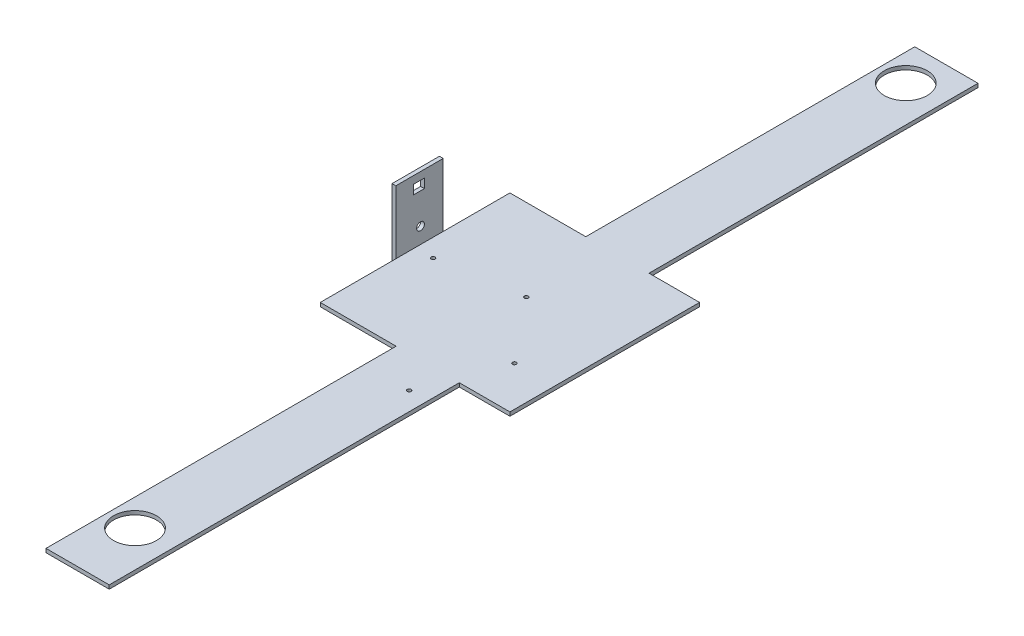
SolidWorks part; units mm, degrees
ref_plane "Front Plane" through (0, 0, 0) normal (0, 0, 1) x (1, 0, 0)
ref_plane "Top Plane" through (0, 0, 0) normal (0, 1, 0) x (1, 0, 0)
ref_plane "Right Plane" through (0, 0, 0) normal (1, 0, 0) x (0, 0, -1)
sketch "Sketch1" plane through (0, 0, 0) normal (0, 1, 0) x (1, 0, 0)
  line L0 (-140.4501, 142.2012) -> (-100.4501, 142.2012)
  line L1 (-250.4501, 142.2012) -> (-200.4501, 142.2012)
  line L2 (-250.4501, 142.2012) -> (-250.4501, -7.7988)
  line L3 (-250.4501, -7.7988) -> (-190.4501, -7.7988)
  line L4 (-100.4501, 142.2012) -> (-100.4501, -7.7988)
  line L6 (-140.4501, -7.7988) -> (-140.4501, -284.718)
  line L7 (-140.4501, -284.718) -> (-190.4501, -284.718)
  line L8 (-190.4501, -7.7988) -> (-190.4501, -284.718)
  line L13 (-140.4501, -7.7988) -> (-100.4501, -7.7988)
  line L16 (-190.4501, 142.2012) -> (-200.4501, 142.2012)
  line L19 (-190.4501, 142.2012) -> (-190.4501, 402.4081)
  line L20 (-190.4501, 402.4081) -> (-140.4501, 402.4081)
  line L21 (-140.4501, 142.2012) -> (-140.4501, 402.4081)
  circle A2 centre (-169.1084, 373.9535) radius 17
  circle A3 centre (-169.1084, -235.6465) radius 17
  dimension "D5" = 40
  dimension "D6" = 60
  dimension "D1" = 150
  dimension "D2" = 150
  dimension "D3" = 40
  dimension "D4" = 60
extrude "Boss-Extrude1" add sketch "Sketch1" along normal blind 3
sketch "Sketch2" plane through (0, 3, 0) normal (0, 1, 0) x (1, 0, 0)
  line L0 (-250.4501, 67.2012) -> (-58.7112, 67.2012) construction
  line L1 (-250.4501, 142.2012) -> (-250.4501, -7.7988) construction
  line L2 (-220.4501, 142.2012) -> (-220.4501, -12.6798) construction
  line L3 (-190.4501, 142.2012) -> (-250.4501, 142.2012) construction
  circle A0 centre (-236.2001, 67.2012) radius 1.5
  circle A1 centre (-172.5794, 77.3253) radius 1.5
  circle A2 centre (-132.0013, 27.2902) radius 1.5
  circle A3 centre (-155.0439, -32.869) radius 1.5
  circle A4 centre (-218.6646, -42.9932) radius 1.5
  circle A5 centre (-259.2428, 7.0419) radius 1.5
  point P10 (-220.4501, 67.2012)
  point P24 (-195.622, 17.1661)
  dimension "D1" = 15.75
  dimension "D2" = 6
sketch "Sketch3" plane through (-250.4501, 0, 0) normal (-1, 0, 0) x (0, 0, 1)
  line L0 (-142.2012, 3) -> (7.7988, 3) construction
  line L1 (-89.4608, 0) -> (-51.9404, 0)
  line L2 (-89.4608, 0) -> (-89.4608, 53)
  line L3 (-89.4608, 53) -> (-51.9404, 53)
  line L4 (-51.9404, 0) -> (-51.9404, 53)
  line L5 (-142.2012, 0) -> (7.7988, 0) construction
  line L7 (-74.5663, 47.0142) -> (-66.1343, 47.0142)
  line L8 (-74.5663, 47.0142) -> (-74.5663, 39.7713)
  line L9 (-74.5663, 39.7713) -> (-66.1343, 39.7713)
  line L10 (-66.1343, 47.0142) -> (-66.1343, 39.7713)
  circle A0 centre (-71.4852, 15.5174) radius 3.0811
  dimension "D1" = 50
  dimension "D2" = 0
extrude "Boss-Extrude2" add sketch "Sketch3" along normal blind 3
sketch "Sketch4" plane through (-253.4501, 0, 0) normal (-1, 0, 0) x (0, 0, 1)
extrude "Cut-Extrude1" cut sketch "Sketch2" against normal blind 3
